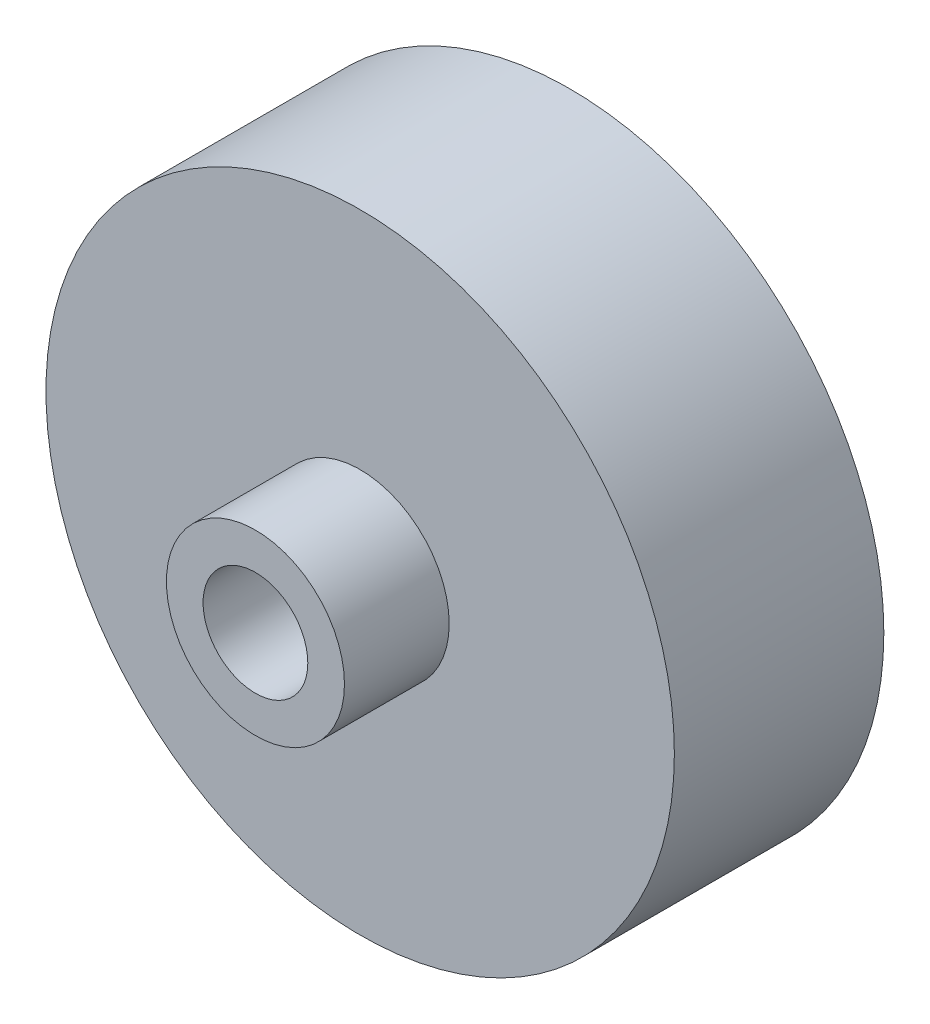
SolidWorks part; units mm, degrees
ref_plane "Front Plane" through (0, 0, 0) normal (0, 0, 1) x (1, 0, 0)
ref_plane "Top Plane" through (0, 0, 0) normal (0, 1, 0) x (1, 0, 0)
ref_plane "Right Plane" through (0, 0, 0) normal (1, 0, 0) x (0, 0, -1)
sketch "Sketch1" plane through (0, 0, 0) normal (0, 0, 1) x (1, 0, 0)
  circle A0 centre (0, 0) radius 30
  circle A1 centre (0, 0) radius 5
  dimension "D1" = 60
  dimension "D2" = 10
extrude "PulleyBody" add sketch "Sketch1" along normal blind 20
sketch "Sketch2" plane through (0, 0, 20) normal (0, 0, 1) x (1, 0, 0)
  circle A0 centre (0, 0) radius 5 construction
  circle A1 centre (0, 0) radius 5
  circle A2 centre (0, 0) radius 8.5
  dimension "D1" = 17
extrude "ConectorStub" add sketch "Sketch2" along normal blind 10
